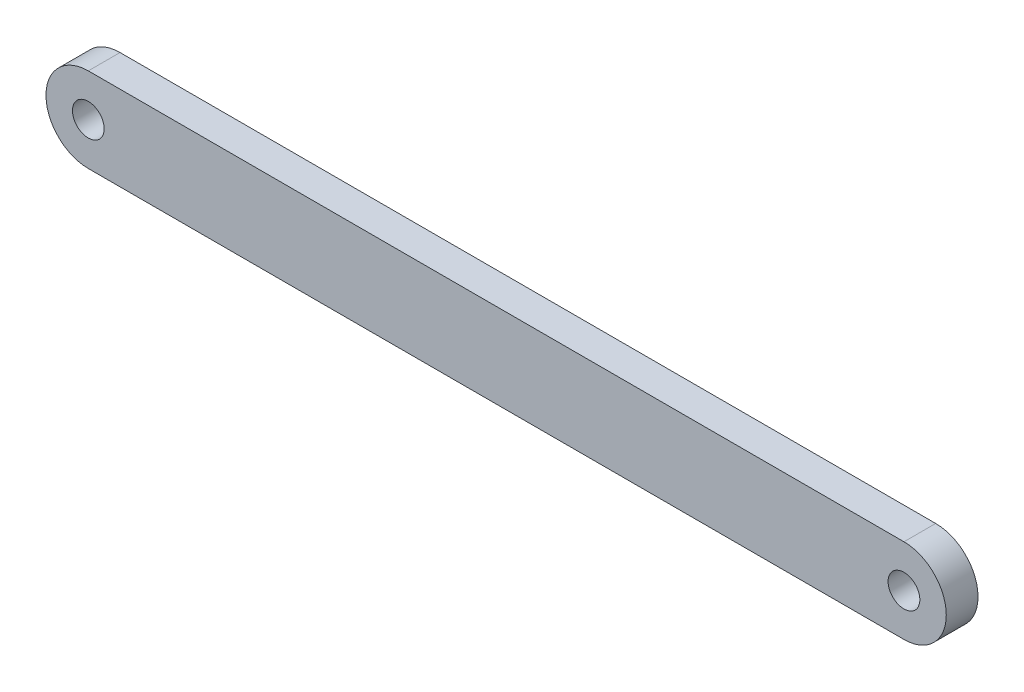
SolidWorks part; units mm, degrees
ref_plane "Front Plane" through (0, 0, 0) normal (0, 0, 1) x (1, 0, 0)
ref_plane "Top Plane" through (0, 0, 0) normal (0, 1, 0) x (1, 0, 0)
ref_plane "Right Plane" through (0, 0, 0) normal (1, 0, 0) x (0, 0, -1)
sketch "Sketch1" plane through (0, 0, 0) normal (0, 0, 1) x (1, 0, 0)
  line L0 (0, 0) -> (122.428, 0) construction
  line L1 (0, 6.35) -> (122.428, 6.35)
  line L2 (0, -6.35) -> (122.428, -6.35)
  arc A0 (0, 6.35) -> (0, -6.35) centre (0, 0) ccw
  arc A1 (122.428, -6.35) -> (122.428, 6.35) centre (122.428, 0) ccw
  circle A2 centre (0, 0) radius 2.3813
  circle A3 centre (122.428, 0) radius 2.3813
  point P3 (61.214, 0)
  dimension "D3" = 4.7625
  dimension "D4" = 4.7625
  dimension "D1" = 12.7
  dimension "D2" = 122.428
extrude "Boss-Extrude1" add sketch "Sketch1" along normal blind 4.7625
